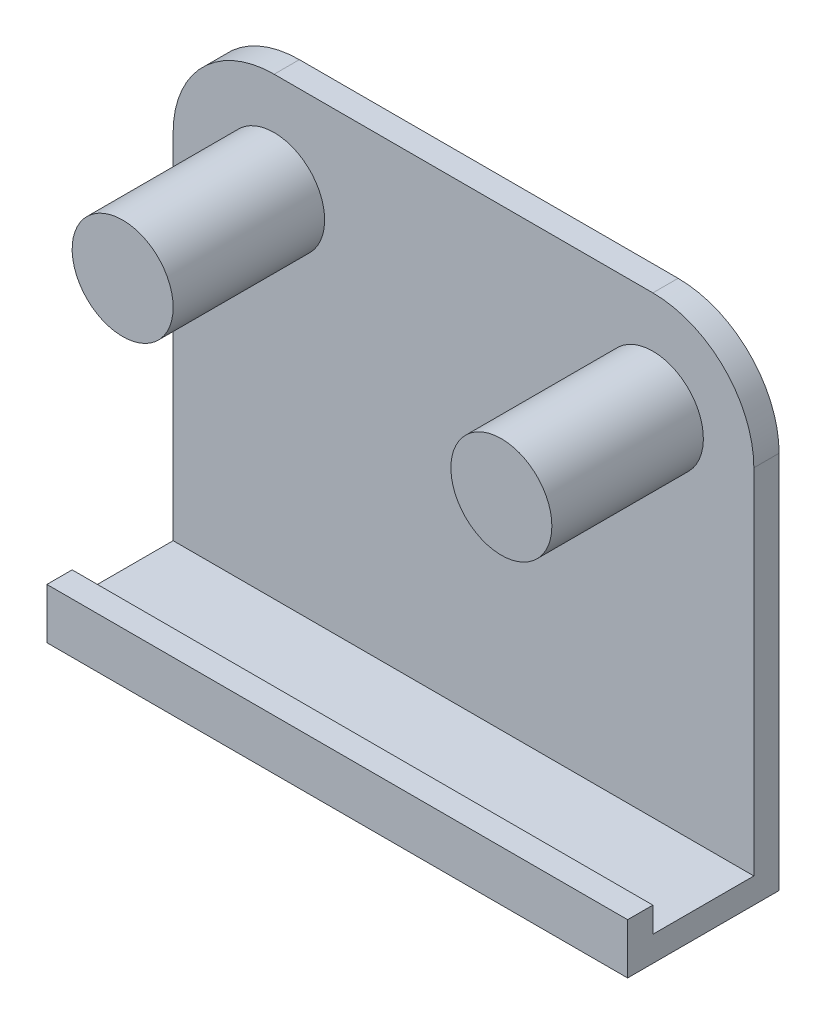
SolidWorks part; units mm, degrees
ref_plane "Front Plane" through (0, 0, 0) normal (0, 0, 1) x (1, 0, 0)
ref_plane "Top Plane" through (0, 0, 0) normal (0, 1, 0) x (1, 0, 0)
ref_plane "Right Plane" through (0, 0, 0) normal (1, 0, 0) x (0, 0, -1)
sketch "Sketch1" plane through (0, 0, 0) normal (1, 0, 0) x (0, 0, -1)
  line L0 (0, 95) -> (0, 0)
  line L1 (0, 0) -> (-30, 0)
  line L2 (-30, 0) -> (-30, 10)
  dimension "D1" = 95
  dimension "D2" = 30
  dimension "D3" = 10
extrude "Extrude-Thin1" add sketch "Sketch1" along normal blind 115 thin
fillet "Fillet1" radius 20 2 edges at (0, 95, 2.5) (115, 95, 2.5)
sketch "Sketch2" plane through (0, 0, 5) normal (0, 0, 1) x (1, 0, 0)
  circle A0 centre (20, 75) radius 10
  circle A1 centre (95, 75) radius 10
  arc A2 (115, 75) -> (95, 95) centre (95, 75) ccw construction
  arc A3 (20, 95) -> (0, 75) centre (20, 75) ccw construction
  dimension "D1" = 20
extrude "Boss-Extrude1" add sketch "Sketch2" along normal blind 30
